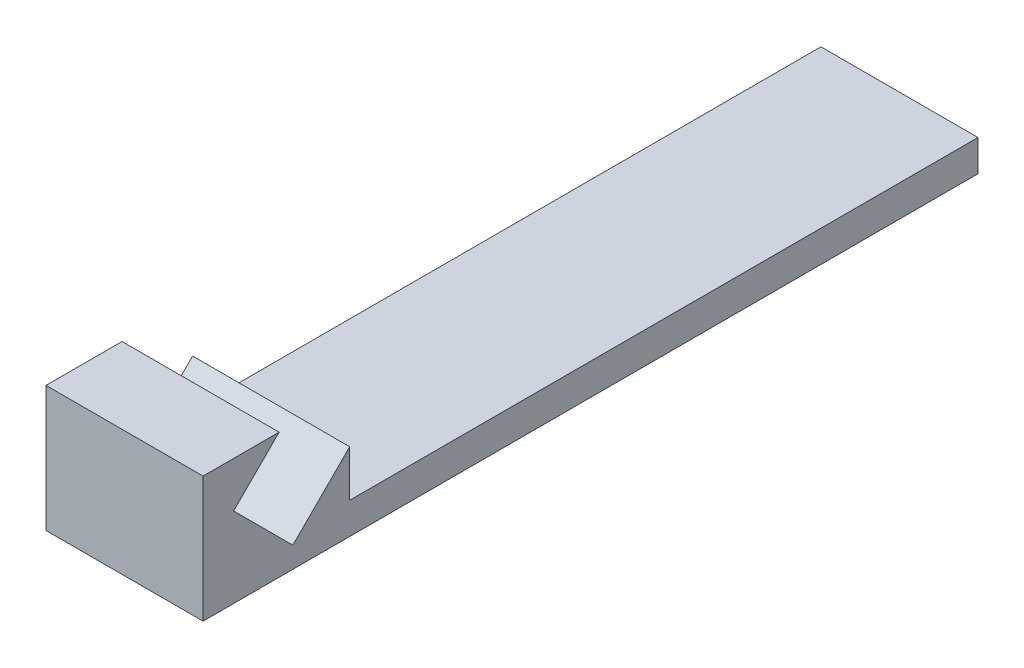
SolidWorks part; units mm, degrees
ref_plane "Front Plane" through (0, 0, 0) normal (0, 0, 1) x (1, 0, 0)
ref_plane "Top Plane" through (0, 0, 0) normal (0, 1, 0) x (1, 0, 0)
ref_plane "Right Plane" through (0, 0, 0) normal (1, 0, 0) x (0, 0, -1)
sketch "Sketch1" plane through (0, 0, 0) normal (1, 0, 0) x (0, 0, -1)
  line L0 (-14, 9) -> (0, 9)
  line L1 (-14, 9) -> (-14, -3)
  line L2 (-14, -3) -> (0, -3)
  line L3 (0, 9) -> (0, -3)
  line L4 (0, 0) -> (60, 0)
  line L5 (0, 0) -> (0, -3)
  line L6 (0, -3) -> (60, -3)
  line L7 (60, 0) -> (60, -3)
  point P7 (0, 3)
  dimension "D1" = 3
  dimension "D2" = 14
  dimension "D3" = 60
  dimension "D4" = 12
extrude "Boss-Extrude1" add sketch "Sketch1" against normal blind 15 contours L3 L0 L1 L2 | L7 L4 L3 L6
split line "Split Line1"
sketch "Sketch6" plane through (0, 0, 0) normal (1, 0, 0) x (0, 0, -1)
  line L0 (-6.7411, 9) -> (-11.0843, 4.6569)
  line L1 (-11.0843, 4.6569) -> (-5.4274, -1)
  line L2 (-5.4274, -1) -> (-11.0843, 4.6569) construction
  line L3 (-5.4274, -1) -> (0, 4.4274)
  line L4 (0, 4.4274) -> (0, 9)
  line L5 (0, 9) -> (-6.7411, 9)
  line L6 (-6.9482, 9.5) -> (-11.7914, 4.6569)
  line L7 (-11.7914, 4.6569) -> (-5.4274, -1.7071)
  line L8 (-5.4274, -1.7071) -> (0.5, 4.2203)
  line L9 (0.5, 4.2203) -> (0.5, 9.5)
  line L10 (0.5, 9.5) -> (-6.9482, 9.5)
  line M2 (0, 4.4274) -> (-5.4274, -1)
  line M3 (-5.4274, -1) -> (-11.0843, 4.6569)
  line M4 (-11.0843, 4.6569) -> (-6.7411, 9)
  dimension "D1" = 0.5
extrude "Cut-Extrude1" cut sketch "Sketch6" against normal through all contours L4 L5 M4 M3 M2
